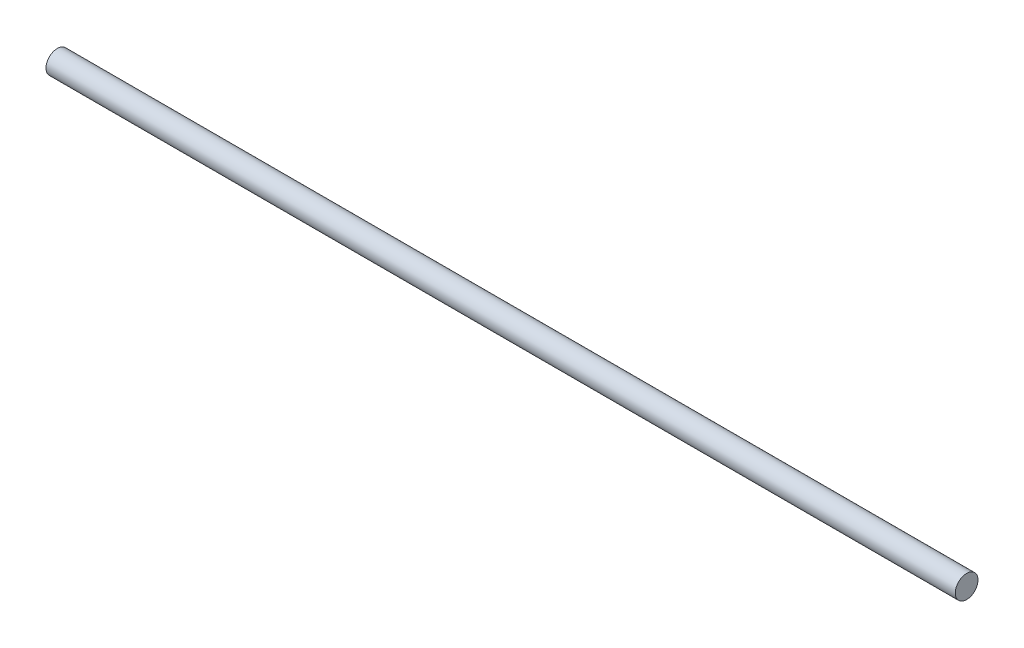
SolidWorks part; units mm, degrees
ref_plane "Front Plane" through (0, 0, 0) normal (0, 0, 1) x (1, 0, 0)
ref_plane "Top Plane" through (0, 0, 0) normal (0, 1, 0) x (1, 0, 0)
ref_plane "Right Plane" through (0, 0, 0) normal (1, 0, 0) x (0, 0, -1)
sketch "Sketch1" plane through (0, 0, 0) normal (1, 0, 0) x (0, 0, -1)
  circle A0 centre (0, 0) radius 12.5001
extrude "Boss-Extrude1" add sketch "Sketch1" along normal mid plane 1000
